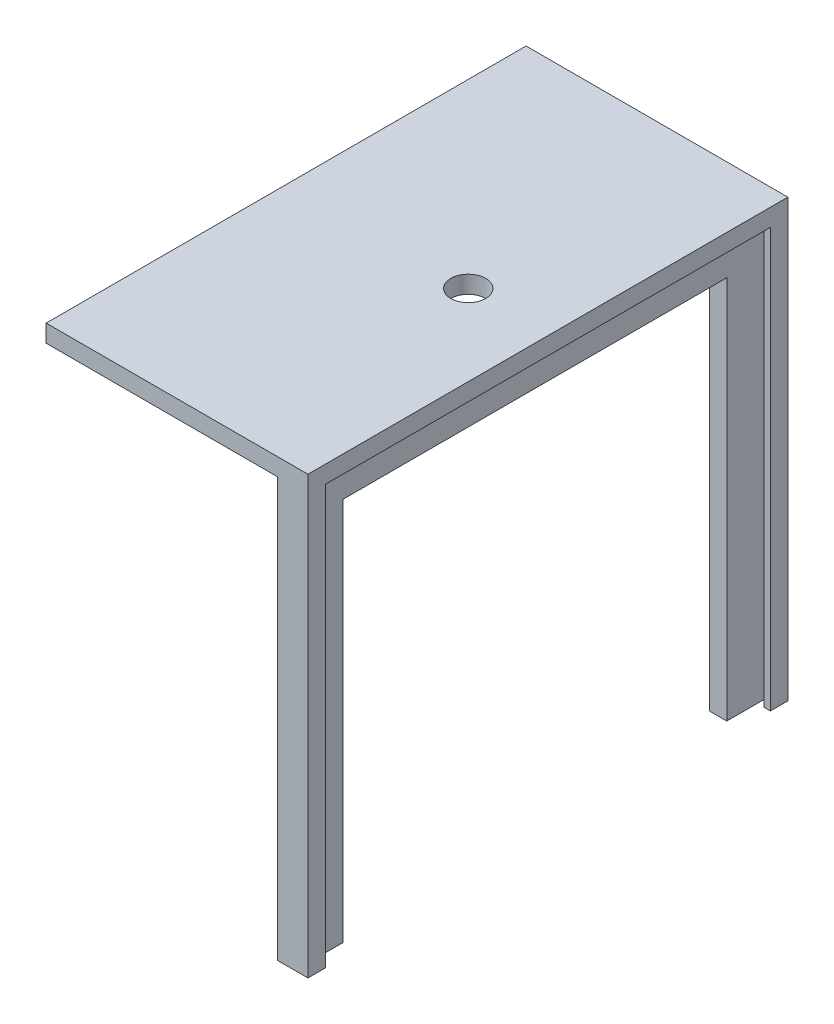
SolidWorks part; units mm, degrees
ref_plane "Front Plane" through (0, 0, 0) normal (0, 0, 1) x (1, 0, 0)
ref_plane "Top Plane" through (0, 0, 0) normal (0, 1, 0) x (1, 0, 0)
ref_plane "Right Plane" through (0, 0, 0) normal (1, 0, 0) x (0, 0, -1)
sketch "Sketch1" plane through (0, 0, 0) normal (0, 1, 0) x (1, 0, 0)
  line L1 (-36.38, 55) -> (20.62, 55)
  line L2 (-36.38, 55) -> (-36.38, -55)
  line L3 (-36.38, -55) -> (20.62, -55)
  line L4 (20.62, 55) -> (20.62, -55)
  line L5 (16.62, -55) -> (16.62, -51) construction
  line L6 (-36.38, -52.5) -> (-36.38, 52.5) construction
  point P6 (-36.38, 0)
  dimension "D1" = 4
  dimension "D2" = 110
extrude "Boss-Extrude1" add sketch "Sketch1" along normal blind 4
sketch "Sketch2" plane through (0, 0, 0) normal (0, -1, 0) x (1, 0, 0)
  line L1 (20.62, 55) -> (16.62, 55)
  line L2 (20.62, 55) -> (20.62, -55)
  line L3 (20.62, -55) -> (16.62, -55)
  line L4 (16.62, 55) -> (16.62, -55)
  line L5 (20.62, -55) -> (-36.38, -55) construction
extrude "Boss-Extrude2" add sketch "Sketch2" along normal up to surface (96 mm away)
sketch "Sketch3" plane through (-32.38, 0, 0) normal (1, 0, 0) x (0, 0, -1)
  line L0 (45, 0) -> (45, -5)
  line L1 (55, 0) -> (-55, 0) construction
  line L2 (45, 0) -> (35, 0)
  line L3 (35, 0) -> (35, -5)
  line L4 (55, 4) -> (55, 0) construction
  line L5 (0, 10.2869) -> (0, -12.0401) construction
  line L6 (-35, 0) -> (-35, -5)
  line L7 (-45, 0) -> (-35, 0)
  line L8 (-45, 0) -> (-45, -5)
  arc A0 (45, -5) -> (35, -5) centre (40, -5) cw
  circle A1 centre (40, -5) radius 3.41
  circle A2 centre (-40, -5) radius 3.41
  arc A3 (-45, -5) -> (-35, -5) centre (-40, -5) ccw
  dimension "D2" = 5
  dimension "D3" = 6.82
  dimension "D1" = 10
  dimension "D4" = 5
extrude "Boss-Extrude3" add sketch "Sketch3" along normal blind 4
sketch "Sketch4" plane through (0, 4, 0) normal (0, 1, 0) x (1, 0, 0)
  circle A2 centre (5.12, 0.25) radius 4
  circle A3 centre (5.12, 0.25) radius 2.25 construction
  dimension "D1" = 8
extrude "Cut-Extrude1" cut sketch "Sketch4" against normal up to next
sketch "Sketch5" plane through (20.62, 0, 0) normal (1, 0, 0) x (0, 0, -1)
  line L0 (55, -96) -> (-55, -96) construction
  line L1 (-44, -96) -> (44, -96)
  line L2 (-44, -96) -> (-44, -8)
  line L3 (-44, -8) -> (44, -8)
  line L4 (44, -96) -> (44, -8)
  line L6 (-55, 4) -> (55, 4) construction
  point P6 (0, 4)
  point P9 (0, -8)
  dimension "D1" = 88
  dimension "D2" = 88
extrude "Cut-Extrude2" cut sketch "Sketch5" against normal up to next
sketch "Sketch6" plane through (0, 0, 0) normal (0, 0, 1) x (1, 0, 0)
  line L0 (20.62, 2) -> (20.62, 4)
  line L1 (20.62, 4) -> (20.62, -96) construction
  line L2 (20.62, 4) -> (23.62, 4)
  line L3 (23.62, 4) -> (23.62, 0)
  line L4 (23.62, 0) -> (22.12, 0)
  line L5 (22.12, 0) -> (22.12, 2)
  line L6 (22.12, 2) -> (20.62, 2)
  line L7 (-36.38, 4) -> (20.62, 4) construction
  dimension "D1" = 2
  dimension "D2" = 2
  dimension "D3" = 3
  dimension "D4" = 1.5
extrude "Boss-Extrude4" add sketch "Sketch6" along normal mid plane 110
sketch "Sketch7" plane through (0, 4, 0) normal (0, 1, 0) x (1, 0, 0)
  line L0 (23.62, 55) -> (20.62, 55)
  line L1 (23.62, 55) -> (-36.38, 55) construction
  line L2 (20.62, 55) -> (20.62, 53)
  line L3 (20.62, 53) -> (22.12, 53)
  line L4 (22.12, 53) -> (22.12, 51)
  line L5 (22.12, 51) -> (23.62, 51)
  line L6 (23.62, -55) -> (23.62, 55) construction
  line L7 (23.62, 51) -> (23.62, 55)
  line L8 (0, 0) -> (38.0376, 0) construction
  line L9 (23.62, -51) -> (23.62, -55)
  line L10 (22.12, -51) -> (23.62, -51)
  line L11 (22.12, -53) -> (22.12, -51)
  line L12 (20.62, -53) -> (22.12, -53)
  line L13 (20.62, -55) -> (20.62, -53)
  line L14 (23.62, -55) -> (20.62, -55)
  dimension "D1" = 1.5
  dimension "D2" = 3
  dimension "D3" = 2
  dimension "D4" = 2
extrude "Boss-Extrude5" add sketch "Sketch7" against normal blind 100
equation "\"Printed Hole Size\"= 6.5"
equation "\"CAD Hole Size\"= 0.9683 * \"Printed Hole Size\" + 0.5265"
